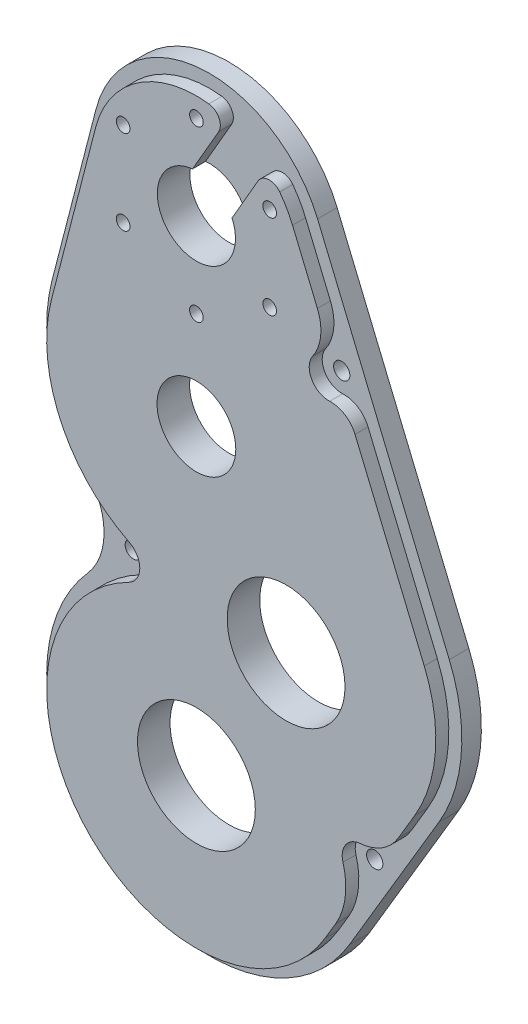
SolidWorks part; units mm, degrees
ref_plane "Front Plane" through (0, 0, 0) normal (0, 0, 1) x (1, 0, 0)
ref_plane "Top Plane" through (0, 0, 0) normal (0, 1, 0) x (1, 0, 0)
ref_plane "Right Plane" through (0, 0, 0) normal (1, 0, 0) x (0, 0, -1)
sketch "Sketch1" plane through (0, 0, 0) normal (0, 0, 1) x (1, 0, 0)
  line L0 (0, 0) -> (0, -74.44) construction
  line L1 (0, -28) -> (13.7779, -51.22) construction
  line L2 (13.7779, -51.22) -> (0, -74.44) construction
  line L3 (-17.4284, 4.5) -> (-24.2061, -21.75)
  line L4 (-25, -39) -> (38.7779, -39) construction
  line L5 (35.2779, -63.9774) -> (21.5, -87.1974)
  line L6 (36.8516, -41.5967) -> (16.613, 6.9288)
  line L7 (-25, -74.44) -> (-25, -28) construction
  line L8 (38.7779, 1.4363) -> (38.7779, -91.7608) construction
  line L9 (-18, 7.4714) -> (-18, -38.8167) construction
  line L10 (-25, -36) -> (38.7779, -36) construction
  circle A0 centre (0, 0) radius 9 construction
  circle A1 centre (0, -28) radius 21 construction
  circle A2 centre (0, -74.44) radius 21 construction
  circle A3 centre (13.7779, -51.22) radius 21 construction
  circle A4 centre (0, 0) radius 9 construction
  circle A6 centre (0, 13) radius 1 construction
  arc A12 (-17.4284, 4.5) -> (16.613, 6.9288) centre (0, 0) ccw construction
  arc A13 (-18.706, -57.8543) -> (21.5, -87.1974) centre (0, -74.44) ccw
  arc A14 (35.2779, -63.9774) -> (36.8516, -41.5967) centre (13.7779, -51.22) ccw
  circle A18 centre (0, 0) radius 4.5 construction
  arc A19 (16.613, 6.9288) -> (-17.4284, 4.5) centre (0, 0) ccw construction
  arc A20 (16.613, 6.9288) -> (-17.4284, 4.5) centre (0, 0) ccw
  circle A21 centre (0, 0) radius 6
  arc A22 (-24.2061, -21.75) -> (-18.706, -44.5857) centre (0, -28) ccw
  circle A23 centre (0, -28) radius 6.05
  circle A24 centre (13.7779, -51.22) radius 9.05
  circle A25 centre (0, -74.44) radius 9.05
  circle A26 centre (0, 13) radius 1.05
  circle A27 centre (11.2583, 6.5) radius 1.05
  circle A28 centre (11.2583, -6.5) radius 1.05
  circle A29 centre (0, -13) radius 1.05
  circle A30 centre (-11.2583, -6.5) radius 1.05
  circle A31 centre (-11.2583, 6.5) radius 1.05
  arc A32 (-18.706, -57.8543) -> (-18.706, -44.5857) centre (-26.1884, -51.22) ccw
  point P13 (0, -2.75)
  point P48 (0, 0)
  dimension "D1" = 18
  dimension "D4" = 12.1
  dimension "D5" = 18.1
  dimension "D6" = 50
  dimension "D7" = 50
  dimension "D8" = 18.1
  dimension "D9" = 6
  dimension "D10" = 3
  dimension "D2" = 28
  dimension "D3" = 74.44
extrude "Boss-Extrude1" add sketch "Sketch1" along normal blind 5
sketch "Sketch2" plane through (0, 0, 5) normal (0, 0, 1) x (1, 0, 0)
  line L1 (9.4683, 9.3996) -> (5.4678, 2.4705)
  line L2 (3.4061, 12.8996) -> (-0.5944, 5.9705)
  line L3 (16.613, 6.9288) -> (36.8516, -41.5967)
  line L4 (16.613, 6.9288) -> (36.8516, -41.5967)
  line L5 (35.2779, -63.9774) -> (21.5, -87.1974)
  line L6 (35.2779, -63.9774) -> (21.5, -87.1974)
  line L7 (-24.2061, -21.75) -> (-17.4284, 4.5)
  line L8 (-24.2061, -21.75) -> (-17.4284, 4.5)
  line L9 (14.7671, 6.1589) -> (18.5855, -2.9963)
  line L10 (33.5579, -62.9568) -> (31.009, -67.2525)
  line L11 (-22.2697, -22.25) -> (-15.4919, 4)
  line L12 (24.3694, -16.8643) -> (35.0057, -42.3665)
  line L13 (14.7671, 6.1589) -> (35.0057, -42.3665) construction
  line L14 (21.416, -83.4195) -> (19.78, -86.1768)
  line L15 (33.5579, -62.9568) -> (19.78, -86.1768) construction
  arc A0 (-0.5944, 5.9705) -> (5.4678, 2.4705) centre (0, 0) cw
  arc A1 (3.4061, 12.8996) -> (1.9132, 15.8852) centre (1.6741, 13.8996) ccw
  arc A2 (1.9132, 15.8852) -> (-15.4919, 4) centre (0, 0) ccw
  arc A3 (14.7671, 6.1589) -> (-15.4919, 4) centre (0, 0) ccw construction
  arc A4 (12.8004, 9.5995) -> (9.4683, 9.3996) centre (11.2003, 8.3996) ccw
  arc A5 (35.2779, -63.9774) -> (36.8516, -41.5967) centre (13.7779, -51.22) ccw
  arc A6 (35.2779, -63.9774) -> (36.8516, -41.5967) centre (13.7779, -51.22) ccw
  arc A7 (-18.706, -57.8543) -> (21.5, -87.1974) centre (0, -74.44) ccw
  arc A8 (-18.706, -57.8543) -> (21.5, -87.1974) centre (0, -74.44) ccw
  arc A9 (-18.706, -57.8543) -> (-18.706, -44.5857) centre (-26.1884, -51.22) ccw
  arc A11 (-24.2061, -21.75) -> (-18.706, -44.5857) centre (0, -28) ccw
  arc A12 (-24.2061, -21.75) -> (-18.706, -44.5857) centre (0, -28) ccw
  arc A13 (16.613, 6.9288) -> (-17.4284, 4.5) centre (0, 0) ccw
  arc A14 (16.613, 6.9288) -> (-17.4284, 4.5) centre (0, 0) ccw
  arc A15 (33.5579, -62.9568) -> (35.0057, -42.3665) centre (13.7779, -51.22) ccw
  arc A16 (-10.3478, -53.8992) -> (19.78, -86.1768) centre (0, -74.44) ccw
  arc A18 (-22.2697, -22.25) -> (-10.3478, -48.5408) centre (0, -28) ccw
  arc A19 (14.7671, 6.1589) -> (12.8004, 9.5995) centre (0, 0) ccw
  arc A20 (-22.2697, -22.25) -> (-17.4144, -43.0246) centre (0, -28) ccw construction
  arc A21 (-17.4144, -59.4154) -> (19.78, -86.1768) centre (0, -74.44) ccw construction
  arc A22 (-10.3478, -53.8992) -> (-10.3478, -48.5408) centre (-11.6975, -51.22) ccw
  circle A23 centre (-11.6975, -51.22) radius 3 construction
  arc A24 (-18.706, -57.8543) -> (-18.706, -44.5857) centre (-26.1884, -51.22) ccw
  arc A25 (-18.706, -57.8543) -> (-18.706, -44.5857) centre (-22.4188, -51.22) ccw construction
  arc A26 (-17.4144, -59.4154) -> (-17.4144, -43.0246) centre (-22.4188, -51.22) ccw construction
  circle A27 centre (-26.1884, -51.22) radius 10 construction
  circle A28 centre (-11.6975, -51.22) radius 1.25 construction
  circle A29 centre (20.3259, -11.4129) radius 1.25 construction
  arc A30 (17.8656, -9.6963) -> (20.4767, -14.4091) centre (20.3259, -11.4129) ccw
  arc A31 (17.8656, -9.6963) -> (18.5855, -2.9963) centre (12.1249, -5.6908) ccw
  arc A32 (24.3694, -16.8643) -> (20.4767, -14.4091) centre (20.6777, -18.4041) ccw
  circle A33 centre (25.3976, -73.8917) radius 1.25 construction
  arc A34 (25.158, -70.9013) -> (22.5173, -74.7306) centre (25.3976, -73.8917) ccw
  arc A35 (25.158, -70.9013) -> (31.009, -67.2525) centre (24.559, -63.4253) ccw
  arc A36 (21.416, -83.4195) -> (22.5173, -74.7306) centre (11.956, -77.8063) ccw
  dimension "D2" = 6
  dimension "D3" = 14.4909
  dimension "D1" = 2
extrude "Cut-Extrude1" cut sketch "Sketch2" against normal blind 2
sketch "Sketch3" plane through (0, 0, 3) normal (0, 0, 1) x (1, 0, 0)
  circle A0 centre (20.3259, -11.4129) radius 1.25
  circle A1 centre (-11.6975, -51.22) radius 1.25
  circle A2 centre (25.3976, -73.8917) radius 1.25
extrude "Cut-Extrude2" cut sketch "Sketch3" against normal through all
